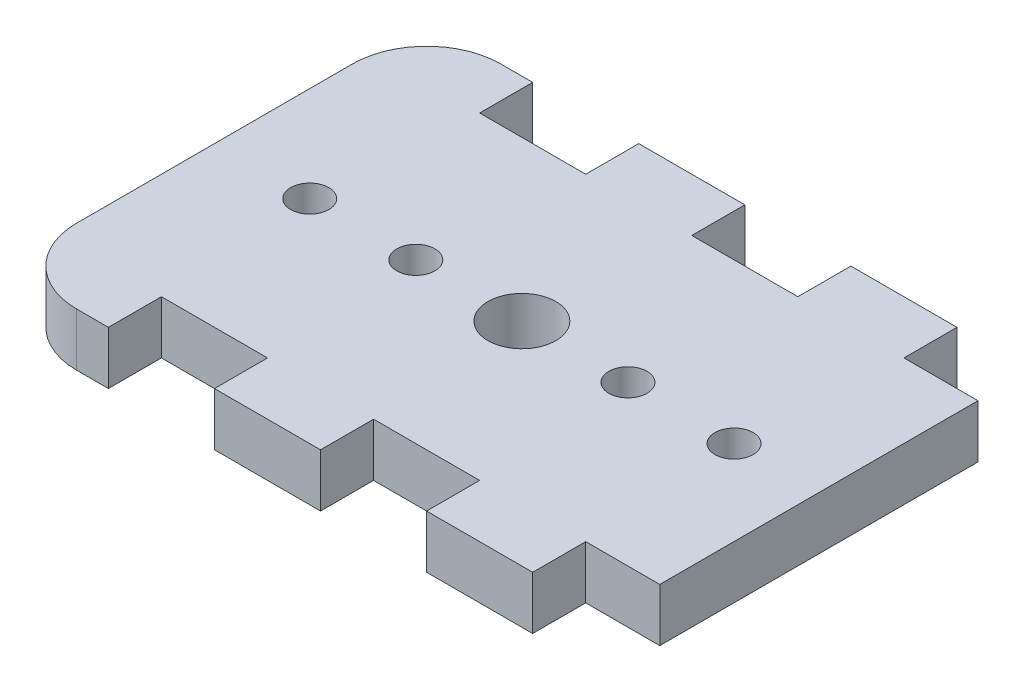
SolidWorks part; units mm, degrees
material "Custom Plastic"
ref_plane "Front Plane" through (0, 0, 0) normal (0, 0, 1) x (1, 0, 0)
ref_plane "Top Plane" through (0, 0, 0) normal (0, 1, 0) x (1, 0, 0)
ref_plane "Right Plane" through (0, 0, 0) normal (1, 0, 0) x (0, 0, -1)
sketch "Sketch1" plane through (0, 0, 0) normal (0, 1, 0) x (1, 0, 0)
  line L0 (-43.18, 19.05) -> (-35.1663, 19.05)
  line L1 (43.18, -25.4) -> (-43.18, -25.4) construction
  line L2 (43.18, -25.4) -> (43.18, 25.4) construction
  line L3 (43.18, 25.4) -> (-43.18, 25.4) construction
  line L4 (-43.18, -25.4) -> (-43.18, 25.4) construction
  line L5 (43.18, -25.4) -> (-43.18, 25.4) construction
  line L6 (43.18, 25.4) -> (-43.18, -25.4) construction
  line L7 (-35.1663, 19.05) -> (-35.1663, 25.4)
  line L8 (-35.1663, 25.4) -> (-22.4663, 25.4)
  line L9 (-22.4663, 25.4) -> (-22.4663, 19.05)
  line L10 (-22.4663, 19.05) -> (-9.7663, 19.05)
  line L11 (-9.7663, 19.05) -> (-9.7663, 25.4)
  line L12 (-9.7663, 25.4) -> (2.9337, 25.4)
  line L13 (2.9337, 25.4) -> (2.9337, 19.05)
  line L14 (2.9337, 19.05) -> (15.6337, 19.05)
  line L15 (15.6337, 19.05) -> (15.6337, 25.4)
  line L16 (15.6337, 25.4) -> (28.3337, 25.4)
  line L17 (28.3337, 25.4) -> (28.3337, 19.05)
  line L18 (28.3337, 19.05) -> (43.18, 19.05)
  line L19 (-43.18, 19.05) -> (-43.18, -19.05)
  line L20 (-43.18, -19.05) -> (-35.1663, -19.05)
  line L21 (-35.1663, -19.05) -> (-35.1663, -25.4)
  line L22 (-35.1663, -25.4) -> (-22.4663, -25.4)
  line L23 (-22.4663, -25.4) -> (-22.4663, -19.05)
  line L24 (-22.4663, -19.05) -> (-9.7663, -19.05)
  line L25 (-9.7663, -19.05) -> (-9.7663, -25.4)
  line L26 (-9.7663, -25.4) -> (2.9337, -25.4)
  line L27 (2.9337, -25.4) -> (2.9337, -19.05)
  line L28 (2.9337, -19.05) -> (15.6337, -19.05)
  line L29 (15.6337, -19.05) -> (15.6337, -25.4)
  line L30 (15.6337, -25.4) -> (28.3337, -25.4)
  line L31 (28.3337, -25.4) -> (28.3337, -19.05)
  line L32 (28.3337, -19.05) -> (43.18, -19.05)
  line L33 (43.18, 19.05) -> (43.18, -19.05)
  point P0 (0, 0)
  dimension "D1" = 50.8
  dimension "D2" = 86.36
  dimension "D3" = 12.7
  dimension "D4" = 6.35
  dimension "D5" = 8.0137
extrude "Main" add sketch "Sketch1" along normal blind 6.35
sketch "Sketch3" plane through (0, 6.35, 0) normal (0, 1, 0) x (1, 0, 0)
  line L0 (-43.18, 19.05) -> (-43.18, -19.05) construction
  line L1 (-23.7584, 0) -> (-11.0584, 0) construction
  line L2 (-11.0584, 0) -> (1.6416, 0) construction
  line L3 (1.6416, 0) -> (14.3416, 0) construction
  line L4 (14.3416, 0) -> (27.0416, 0) construction
  line L5 (1.6416, 0) -> (1.6416, 19.05) construction
  line L6 (15.6337, 19.05) -> (2.9337, 19.05) construction
  line L7 (1.6416, 0) -> (1.6416, -19.05) construction
  line L8 (2.9337, -19.05) -> (15.6337, -19.05) construction
  circle A1 centre (1.6416, 0) radius 4.064
  circle A3 centre (14.3416, 0) radius 2.286
  circle A5 centre (27.0416, 0) radius 2.286
  circle A7 centre (-11.0584, 0) radius 2.286
  circle A9 centre (-23.7584, 0) radius 2.286
  dimension "D1" = 8.128
  dimension "D4" = 4.572
  dimension "D2" = 19.4216
  dimension "D3" = 12.7
extrude "Gear Mount Holes" cut sketch "Sketch3" against normal through all
sketch "Sketch4" plane through (0, 6.35, 0) normal (0, 1, 0) x (1, 0, 0)
  line L0 (28.3337, -19.05) -> (43.18, -19.05) construction
  line L1 (43.18, 19.05) -> (37.2016, 19.05)
  line L2 (43.18, 19.05) -> (43.18, -19.05)
  line L3 (43.18, -19.05) -> (37.2016, -19.05)
  line L4 (37.2016, 19.05) -> (37.2016, -19.05)
  line L5 (-43.18, 19.05) -> (-35.1663, 19.05)
  line L6 (-35.1663, 19.05) -> (-35.1663, -19.05)
  line L7 (-35.1663, -19.05) -> (-43.18, -19.05)
  line L8 (-43.18, -19.05) -> (-43.18, 19.05)
  circle A0 centre (27.0416, 0) radius 2.286 construction
  dimension "D1" = 10.16
extrude "Cut-Extrude2" cut sketch "Sketch4" against normal through all
fillet "Fillet1" radius 8.89 2 edges at (-35.1663, 3.175, -25.4) (-35.1663, 3.175, 25.4)
